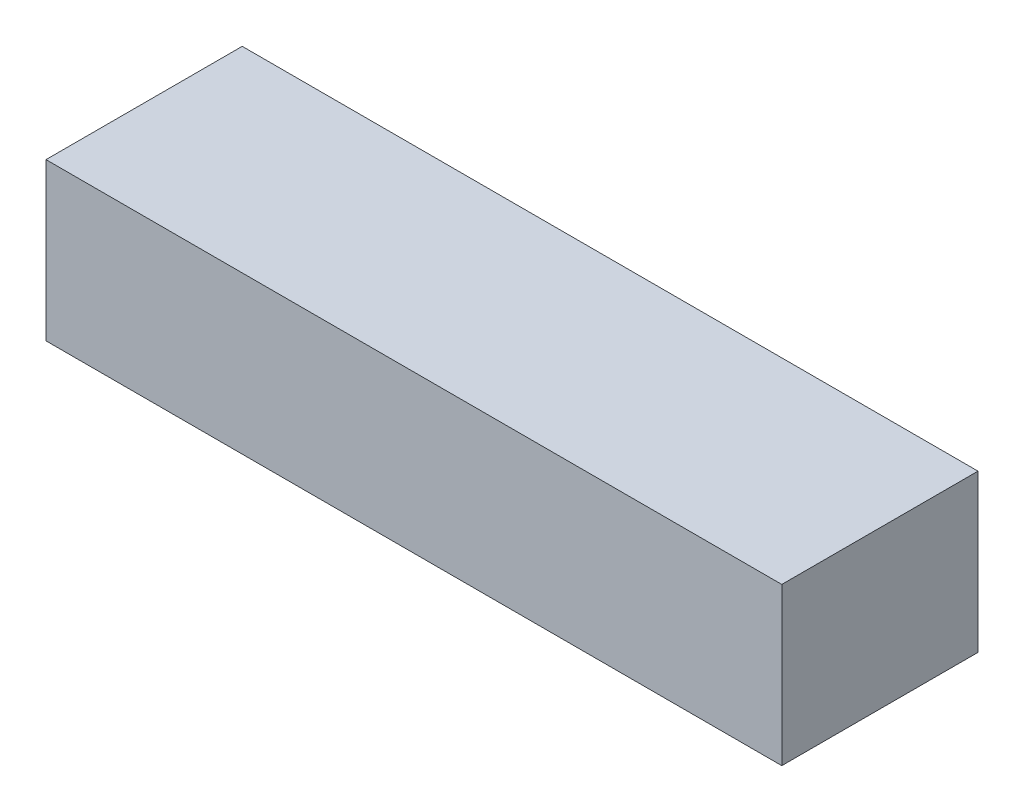
SolidWorks part; units mm, degrees
ref_plane "Front Plane" through (0, 0, 0) normal (0, 0, 1) x (1, 0, 0)
ref_plane "Top Plane" through (0, 0, 0) normal (0, 1, 0) x (1, 0, 0)
ref_plane "Right Plane" through (0, 0, 0) normal (1, 0, 0) x (0, 0, -1)
sketch "Sketch1" plane through (0, 0, 0) normal (0, 1, 0) x (1, 0, 0)
  line L1 (75, -20) -> (-75, -20)
  line L2 (75, -20) -> (75, 20)
  line L3 (75, 20) -> (-75, 20)
  line L4 (-75, -20) -> (-75, 20)
  line L5 (75, -20) -> (-75, 20) construction
  line L6 (75, 20) -> (-75, -20) construction
  point P0 (0, 0)
  dimension "D1" = 150
  dimension "D2" = 40
extrude "Boss-Extrude1" add sketch "Sketch1" along normal blind 30
shell "Shell3" thickness 2
sketch "Sketch3" plane through (0, 0, -20) normal (0, 0, -1) x (-1, 0, 0)
  line L0 (-75, 30) -> (75, 30) construction
  line L1 (-5.0365, 25) -> (14.9635, 25)
  line L2 (-5.0365, 25) -> (-5.0365, 5)
  line L3 (-5.0365, 5) -> (14.9635, 5)
  line L4 (14.9635, 25) -> (14.9635, 5)
  line L5 (-5.0365, 25) -> (14.9635, 5) construction
  line L6 (-5.0365, 5) -> (14.9635, 25) construction
  point P0 (4.9635, 15)
  dimension "D1" = 20
  dimension "D2" = 20
  dimension "D3" = 5
extrude "Cut-Extrude1" cut sketch "Sketch3" against normal blind 5
sketch "Sketch4" plane through (0, 2, 0) normal (0, 1, 0) x (1, 0, 0)
  point P0 (0, 7.6033)
sketch "Sketch6" plane through (0, 2, 0) normal (0, 1, 0) x (1, 0, 0)
  line L0 (-14.7947, 18) -> (-14.7947, 5.398)
  line L1 (73, 18) -> (-73, 18) construction
  line L2 (-14.7947, 5.398) -> (5.0039, 5.398)
  line L3 (5.0039, 5.398) -> (5.0039, 18)
  line L4 (-14.7947, 18) -> (5.0039, 18)
extrude "Boss-Extrude3" add sketch "Sketch6" along normal blind 24
sketch "Sketch7" plane through (0, 30, 0) normal (0, 1, 0) x (1, 0, 0)
  line L1 (-75, 20) -> (75, 20)
  line L2 (-75, 20) -> (-75, -20)
  line L3 (-75, -20) -> (75, -20)
  line L4 (75, 20) -> (75, -20)
extrude "Boss-Extrude4" add sketch "Sketch7" along normal blind 2
sketch "Sketch8" plane through (0, 0, -20) normal (0, 0, -1) x (-1, 0, 0)
  circle A0 centre (-46.5102, 16.5043) radius 1.5
  dimension "D1" = 3
extrude "Boss-Extrude5" add sketch "Sketch8" along normal blind 5
sketch "Sketch9" plane through (0, 0, -20) normal (0, 0, -1) x (-1, 0, 0)
  line L0 (-75, 32) -> (-75, 0) construction
  circle A0 centre (47, 17.0209) radius 1.5
  point P2 (-75, 16)
extrude "Boss-Extrude6" add sketch "Sketch9" along normal blind 5
